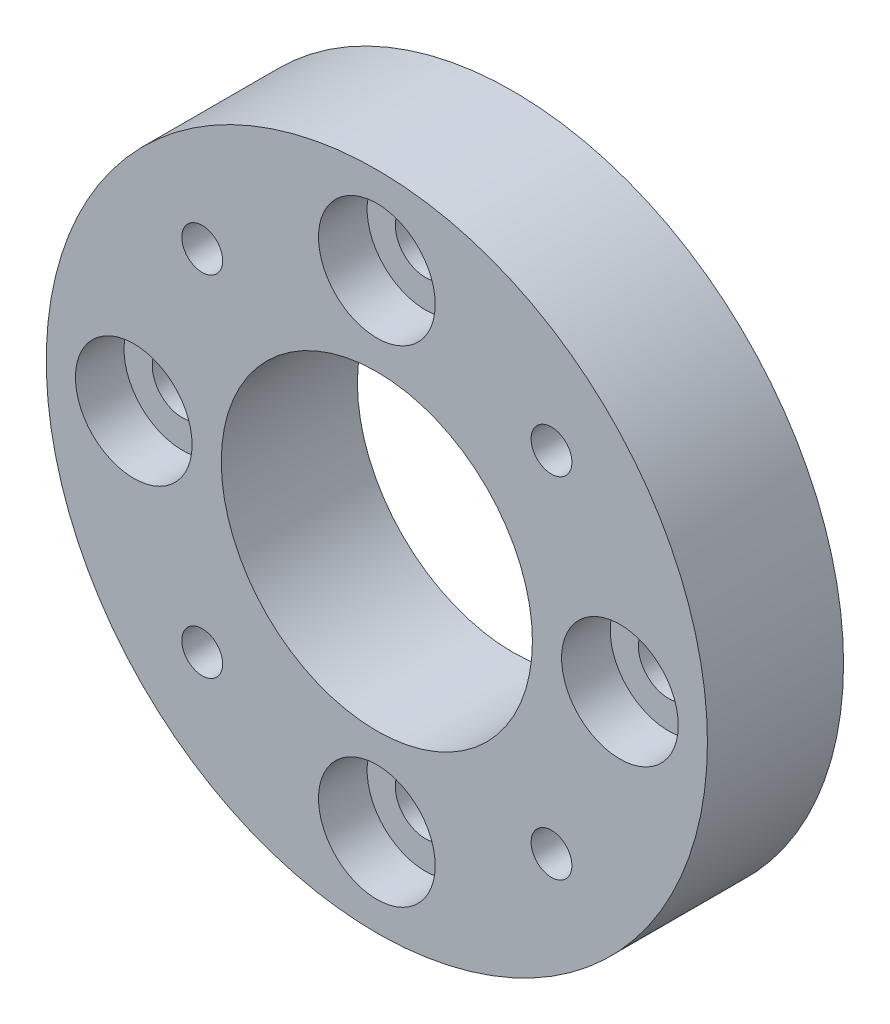
SolidWorks part; units mm, degrees
ref_plane "Front Plane" through (0, 0, 0) normal (0, 0, 1) x (1, 0, 0)
ref_plane "Top Plane" through (0, 0, 0) normal (0, 1, 0) x (1, 0, 0)
ref_plane "Right Plane" through (0, 0, 0) normal (1, 0, 0) x (0, 0, -1)
sketch "Sketch1" plane through (0, 0, 0) normal (0, 0, 1) x (1, 0, 0)
  circle A0 centre (0, 0) radius 17
  circle A1 centre (0, 0) radius 12.7 construction
  circle A2 centre (0, 0) radius 12.5 construction
  circle A3 centre (0, 12.5) radius 1.55
  circle A4 centre (12.5, 0) radius 1.55
  circle A5 centre (0, -12.5) radius 1.55
  circle A6 centre (-12.5, 0) radius 1.55
  circle A7 centre (-8.9803, 8.9803) radius 1.05
  circle A8 centre (8.9803, 8.9803) radius 1.05
  circle A9 centre (8.9803, -8.9803) radius 1.05
  circle A10 centre (-8.9803, -8.9803) radius 1.05
  circle A11 centre (0, 0) radius 8
  point P16 (0, 0)
  point P25 (0, 0)
  dimension "D1" = 4
  dimension "D2" = 4
extrude "Boss-Extrude1" add sketch "Sketch1" along normal blind 7
sketch "Sketch2" plane through (0, 0, 7) normal (0, 0, 1) x (1, 0, 0)
  circle A0 centre (0, 12.5) radius 3
  circle A1 centre (12.5, 0) radius 3
  circle A2 centre (0, -12.5) radius 3
  circle A3 centre (-12.5, 0) radius 3
  point P12 (0, 0)
  dimension "D1" = 4
extrude "Cut-Extrude2" cut sketch "Sketch2" against normal blind 2.5
